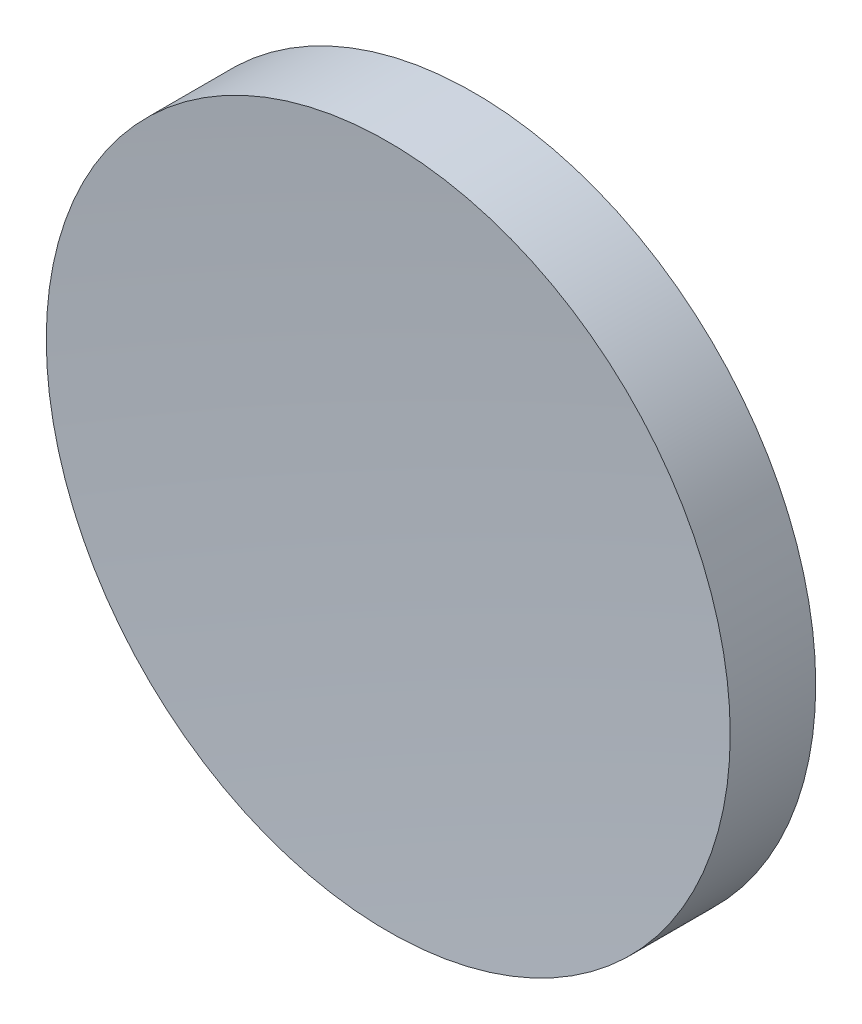
SolidWorks part; units mm, degrees
material "Verre"
ref_plane "Plan de face" through (0, 0, 0) normal (0, 0, 1) x (1, 0, 0)
ref_plane "Plan de dessus" through (0, 0, 0) normal (0, 1, 0) x (1, 0, 0)
ref_plane "Plan de droite" through (0, 0, 0) normal (1, 0, 0) x (0, 0, -1)
sketch "Esquisse1" plane through (0, 0, 0) normal (0, 0, 1) x (1, 0, 0)
  circle A0 centre (0, 0) radius 100
  dimension "D1" = 200
extrude "Boss.-Extru.1" add sketch "Esquisse1" along normal blind 25
sketch "Esquisse2" plane through (0, 0, 0) normal (0, 1, 0) x (1, 0, 0)
  line L0 (0, 0) -> (0, -825) construction
  line L1 (-100, -25) -> (100, -25) construction
  line L2 (0, -1621.8719) -> (0, -21.8719)
  line L3 (0, -1621.8719) -> (1600, -1621.8719)
  arc A0 (1600, -1621.8719) -> (0, -21.8719) centre (0, -1621.8719) ccw
  dimension "D1" = 3200
  dimension "D2" = 800
revolve "Enlèvement de matière-Révolution6" cut sketch "Esquisse2" angle 360 about L0
